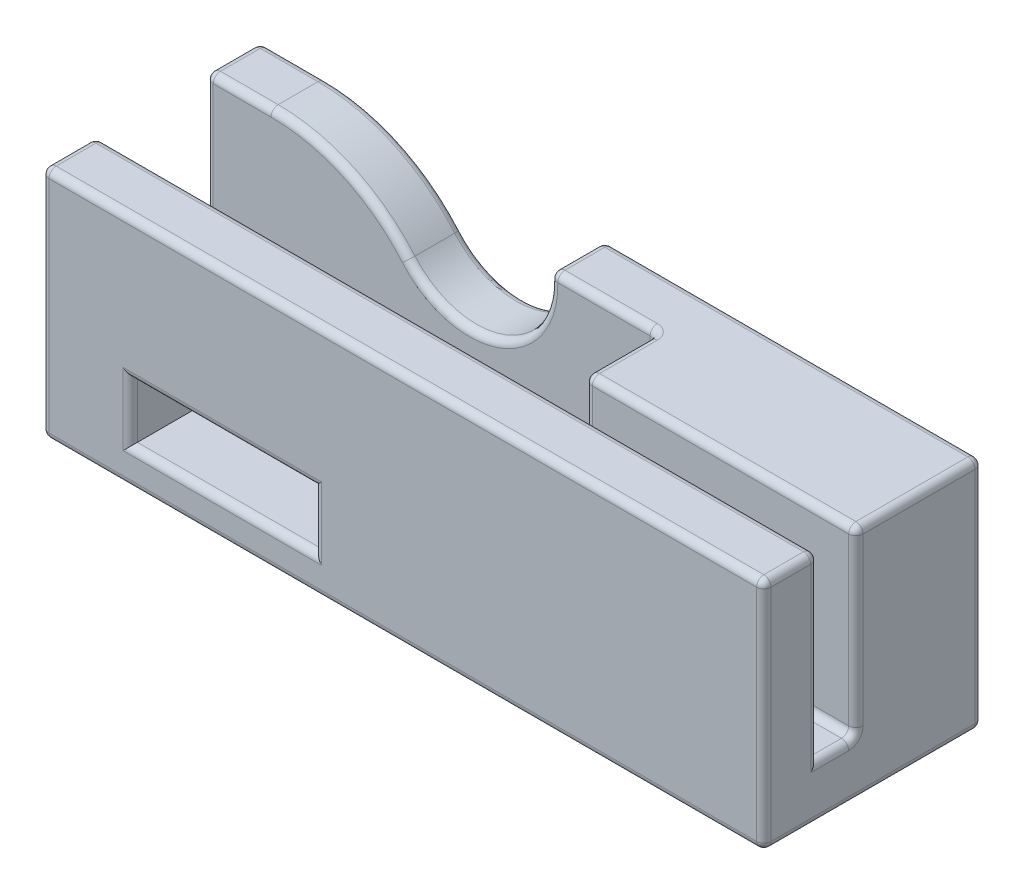
SolidWorks part; units mm, degrees
ref_plane "Front Plane" through (0, 0, 0) normal (0, 0, 1) x (1, 0, 0)
ref_plane "Top Plane" through (0, 0, 0) normal (0, 1, 0) x (1, 0, 0)
ref_plane "Right Plane" through (0, 0, 0) normal (1, 0, 0) x (0, 0, -1)
sketch "Sketch1" plane through (0, 0, 0) normal (0, 1, 0) x (1, 0, 0)
  line L1 (0, 0) -> (40, 0)
  line L2 (0, 0) -> (0, -12.1)
  line L3 (0, -12.1) -> (40, -12.1)
  line L4 (40, 0) -> (40, -12.1)
  dimension "D1" = 12.1
  dimension "D2" = 40
extrude "Boss-Extrude1" add sketch "Sketch1" along normal blind 3
sketch "Sketch2" plane through (0, 3, 0) normal (0, 1, 0) x (1, 0, 0)
  line L0 (40, -12.1) -> (40, 0) construction
  line L1 (0, 0) -> (40, 0)
  line L2 (0, 0) -> (0, -7)
  line L3 (0, -7) -> (40, -7)
  line L4 (40, 0) -> (40, -7)
  line L6 (0, -12.1) -> (40, -12.1)
  line L7 (0, -12.1) -> (0, -9.1)
  line L8 (0, -9.1) -> (40, -9.1)
  line L9 (40, -12.1) -> (40, -9.1)
  dimension "D1" = 7
  dimension "D2" = 3
extrude "Boss-Extrude2" add sketch "Sketch2" along normal blind 10
sketch "Sketch3" plane through (0, 0, 0) normal (0, 0, -1) x (-1, 0, 0)
  line L0 (-40, 0) -> (0, 0) construction
  line L1 (-15.1, 5.2) -> (-4.9, 5.2)
  line L2 (-15.1, 5.2) -> (-15.1, 2)
  line L3 (-15.1, 2) -> (-4.9, 2)
  line L4 (-4.9, 5.2) -> (-4.9, 2)
  point P4 (-10, 2)
  point P7 (-20, 0)
  dimension "D1" = 3.2
  dimension "D2" = 10.2
  dimension "D3" = 10
  dimension "D4" = 2
extrude "Cut-Extrude1" cut sketch "Sketch3" against normal through all
sketch "Sketch5" plane through (0, 0, 0) normal (-1, 0, 0) x (0, 0, 1)
  line L0 (0, 13) -> (7, 13) construction
  line L1 (7, 3) -> (3, 3)
  line L2 (7, 3) -> (7, 13)
  line L3 (7, 13) -> (3, 13)
  line L4 (3, 3) -> (3, 13)
  dimension "D1" = 4
extrude "Cut-Extrude3" cut sketch "Sketch5" against normal blind 25
sketch "Sketch6" plane through (0, 0, 0) normal (0, 0, -1) x (-1, 0, 0)
  circle A0 centre (-14.5887, 12.4597) radius 4.5
  dimension "D1" = 9
extrude "Cut-Extrude4" cut sketch "Sketch6" against normal blind 3
fillet "Fillet3" radius 10 1 edges at (10.1213, 13, 1.5)
fillet "Fillet1" radius 0.4 43 edges at (20, 13, 9.1) (32.5, 13, 7) (40, 13, 10.6) (40, 8, 9.1) (40, 3, 8.05) (40, 8, 7) (40, 13, 3.5) (0, 13, 1.5) (0, 3, 6.05) (0, 8, 9.1) (0, 13, 10.6) (40, 6.5, 0) (1.7997, 13, 0) (29.5281, 13, 0) (0, 6.5, 0) (4.9, 3.6, 0) (10, 5.2, 0) (15.1, 3.6, 0) (10, 2, 0) (40, 0, 6.05) (20, 0, 0) (0, 0, 6.05) (0, 6.5, 12.1) (20, 13, 12.1) (40, 6.5, 12.1) (20, 0, 12.1) (4.9, 3.6, 12.1) (10, 2, 12.1) (15.1, 3.6, 12.1) (10, 5.2, 12.1) (0, 8, 3) (16.4053, 8.3427, 0) (25, 13, 5) (22.0281, 13, 3) (1.7997, 13, 3) (16.4053, 8.3427, 3) (19.0562, 13, 1.5) (7.7684, 12.0895, 0) (32.5, 3, 7) (7.7684, 12.0895, 3) (25, 3, 5) (25, 8, 3) (25, 8, 7)
